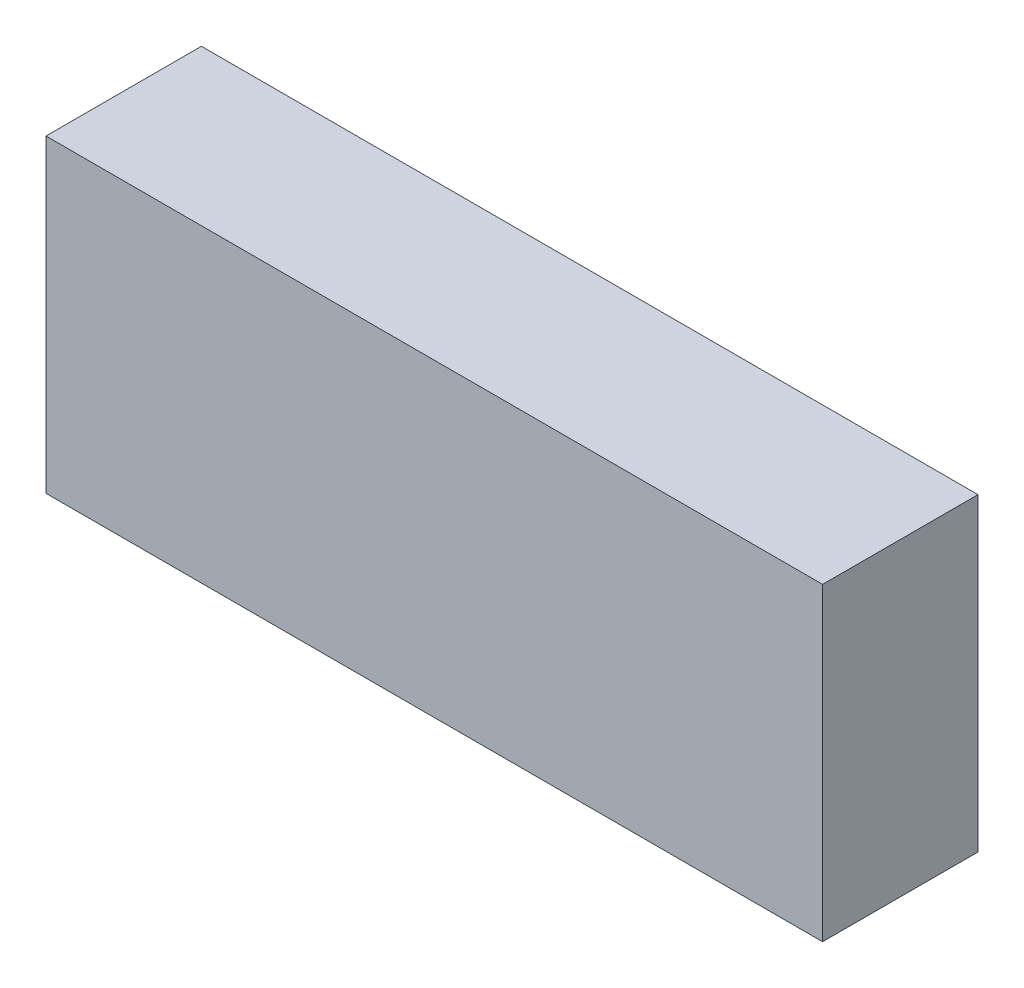
SolidWorks part; units mm, degrees
ref_plane "Front Plane" through (0, 0, 0) normal (0, 0, 1) x (1, 0, 0)
ref_plane "Top Plane" through (0, 0, 0) normal (0, 1, 0) x (1, 0, 0)
ref_plane "Right Plane" through (0, 0, 0) normal (1, 0, 0) x (0, 0, -1)
sketch "Sketch1" plane through (0, 0, 0) normal (0, 0, 1) x (1, 0, 0)
  line L0 (-2.4984, 1.0084) -> (2.4984, 1.0084)
  line L1 (2.4984, 1.0084) -> (2.4984, -0.983)
  line L2 (2.4984, -0.983) -> (-2.4984, -0.983)
  line L3 (-2.4984, -0.983) -> (-2.4984, 1.0084)
extrude "Component_Outline" add sketch "Sketch1" along normal blind 1 separate body
sketch3d "3DSketch1"
  line L0 (0, 0, 0) -> (1, 0, 0)
  line L1 (0, 0, 0) -> (0, 1, 0)
  line L2 (0, 0, 0) -> (0, 0, 1)
  point P0 (0, 0, 0)
